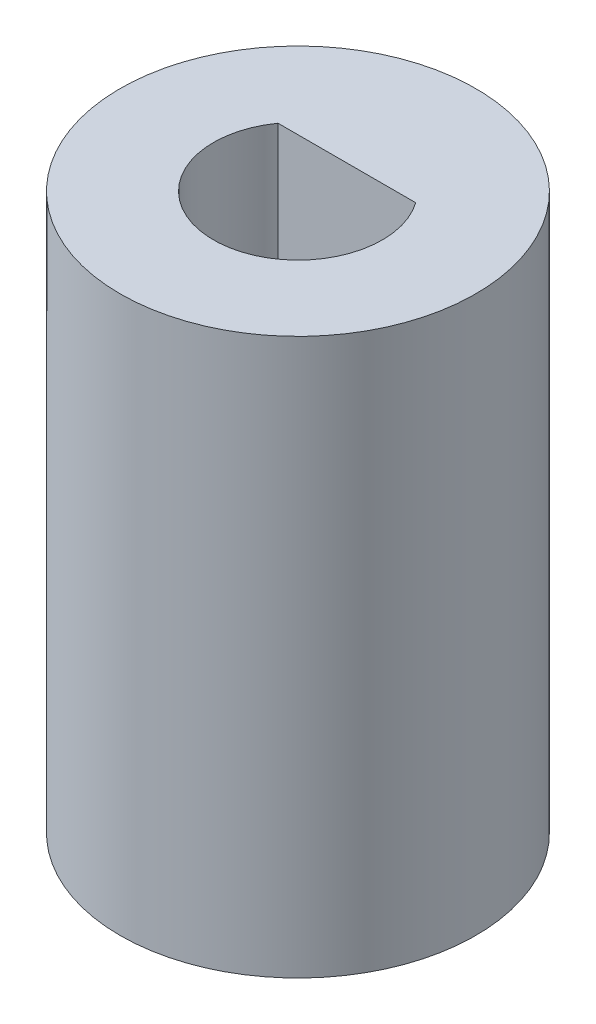
SolidWorks part; units mm, degrees
ref_plane "Front Plane" through (0, 0, 0) normal (0, 0, 1) x (1, 0, 0)
ref_plane "Top Plane" through (0, 0, 0) normal (0, 1, 0) x (1, 0, 0)
ref_plane "Right Plane" through (0, 0, 0) normal (1, 0, 0) x (0, 0, -1)
sketch "Sketch1" plane through (0, 0, 0) normal (0, 1, 0) x (1, 0, 0)
  line L0 (-3.0984, 2.2) -> (3.0984, 2.2)
  circle A0 centre (0, 0) radius 8
  arc A1 (-3.0984, 2.2) -> (3.0984, 2.2) centre (0, 0) ccw
  point P6 (0, 2.2)
  dimension "D1" = 2.2
  dimension "D2" = 16
extrude "Boss-Extrude1" add sketch "Sketch1" along normal blind 25 contours A0 A1 L0
sketch "Sketch2" plane through (0, 0, 0) normal (0, -1, 0) x (1, 0, 0)
  line L0 (0, 0) -> (0, -3) construction
  line L1 (-2.6458, -3) -> (2.6458, -3)
  arc A0 (-2.6458, -3) -> (2.6458, -3) centre (0, 0) cw
  dimension "D2" = 3
extrude "Cut-Extrude1" cut sketch "Sketch2" against normal blind 10
